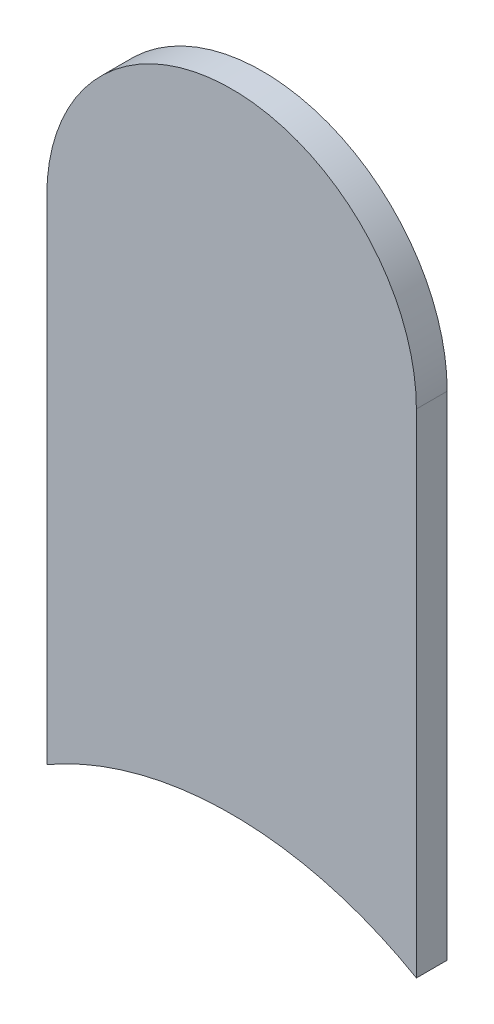
SolidWorks part; units mm, degrees
ref_plane "Front Plane" through (0, 0, 0) normal (0, 0, 1) x (1, 0, 0)
ref_plane "Top Plane" through (0, 0, 0) normal (0, 1, 0) x (1, 0, 0)
ref_plane "Right Plane" through (0, 0, 0) normal (1, 0, 0) x (0, 0, -1)
sketch "Sketch1" plane through (0, 0, 0) normal (0, 0, 1) x (1, 0, 0)
  line L2 (0, 0) -> (0, 50.8)
  line L4 (38.1, 0) -> (38.1, 50.8)
  arc A0 (0, 50.8) -> (38.1, 50.8) centre (19.05, 50.8) cw
  arc A3 (0, 0) -> (38.1, 0) centre (19.05, -32.9956) cw
  dimension "D2" = 38.1
  dimension "D5" = 19.05
  dimension "D6" = 38.1
  dimension "D1" = 38.1
  dimension "D4" = 50.8
extrude "Boss-Extrude1" add sketch "Sketch1" along normal blind 3.175
